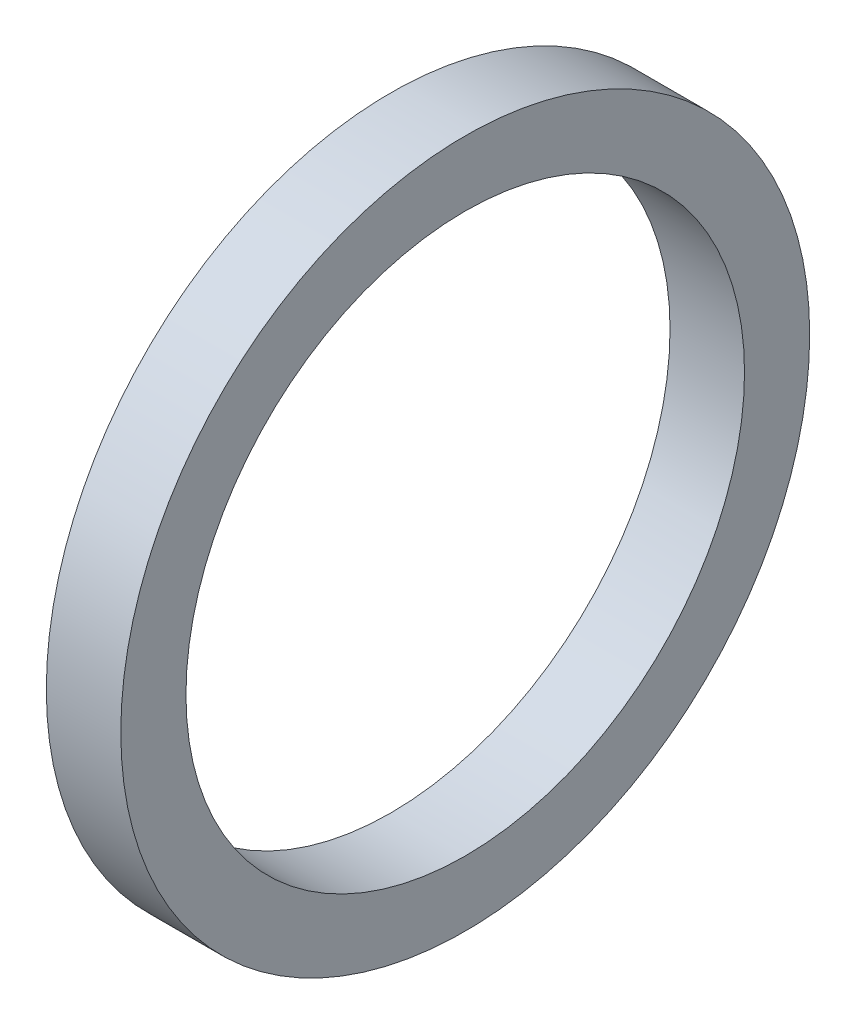
SolidWorks part; units mm, degrees
material "合金钢"
ref_plane "Front" through (0, 0, 0) normal (0, 0, 1) x (1, 0, 0)
ref_plane "Top" through (0, 0, 0) normal (0, 1, 0) x (1, 0, 0)
ref_plane "Right" through (0, 0, 0) normal (1, 0, 0) x (0, 0, -1)
sketch "草图1" plane through (0, 0, 0) normal (0, 0, 1) x (1, 0, 0)
  line L0 (24.6296, 0) -> (0, 0) construction
  line L1 (0, 0) -> (0, 15) construction
  line L2 (0, 15) -> (0, 18.5)
  line L3 (0, 18.5) -> (4, 18.5)
  line L4 (4, 18.5) -> (4, 15)
  line L5 (4, 15) -> (0, 15)
  dimension "D1" = 30
  dimension "D2" = 37
  dimension "D3" = 4
revolve "旋转1" add sketch "草图1" angle 360 about L0
